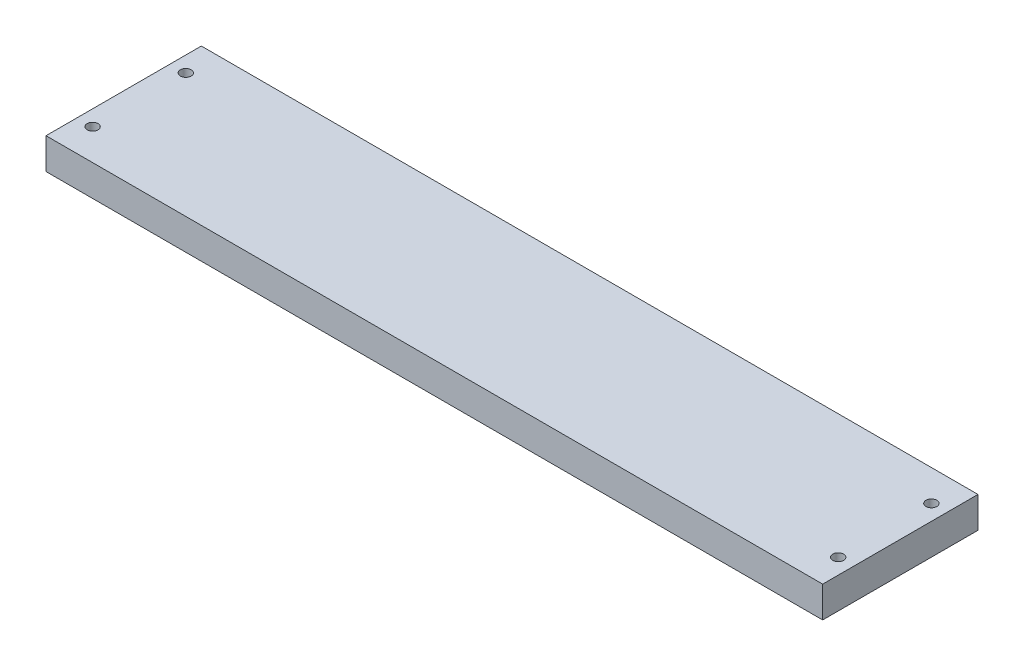
SolidWorks part; units mm, degrees
material "ABS PC"
ref_plane "Спереди" through (0, 0, 0) normal (0, 0, 1) x (1, 0, 0)
ref_plane "Сверху" through (0, 0, 0) normal (0, 1, 0) x (1, 0, 0)
ref_plane "Справа" through (0, 0, 0) normal (1, 0, 0) x (0, 0, -1)
sketch "Sketch1" plane through (0, 0, 0) normal (0, 1, 0) x (1, 0, 0)
  line L1 (0, 0) -> (250, 0)
  line L2 (0, 0) -> (0, 50)
  line L3 (0, 50) -> (250, 50)
  line L4 (250, 0) -> (250, 50)
  circle A0 centre (5, 40) radius 1.75
  circle A1 centre (5, 10) radius 1.75
  circle A2 centre (245, 10) radius 1.75
  circle A3 centre (245, 40) radius 1.75
  dimension "D2" = 3.5
  dimension "D3" = 30
  dimension "D4" = 10
  dimension "D5" = 5
  dimension "D6" = 5
  dimension "D1" = 50
  dimension "D7" = 250
extrude "Boss-Extrude1" add sketch "Sketch1" along normal blind 10
